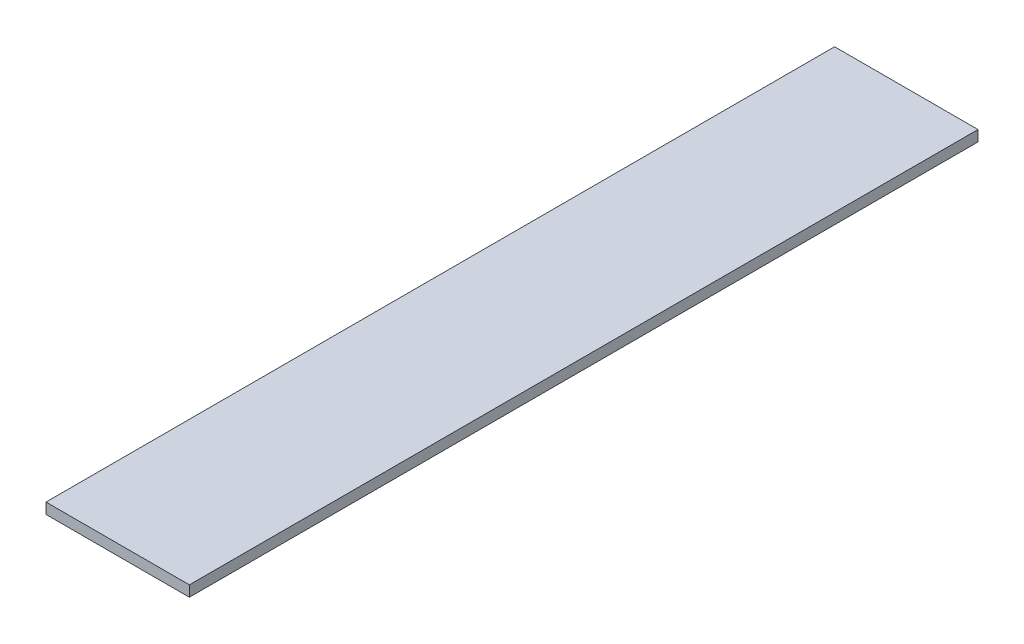
SolidWorks part; units mm, degrees
ref_plane "Front Plane" through (0, 0, 0) normal (0, 0, 1) x (1, 0, 0)
ref_plane "Top Plane" through (0, 0, 0) normal (0, 1, 0) x (1, 0, 0)
ref_plane "Right Plane" through (0, 0, 0) normal (1, 0, 0) x (0, 0, -1)
other "Configuration Table"
sketch "Sketch1" plane through (0, 0, 0) normal (0, 0, 1) x (1, 0, 0)
  line L1 (330, 597) -> (370, 597)
  line L2 (330, 597) -> (330, 600)
  line L3 (330, 600) -> (370, 600)
  line L4 (370, 597) -> (370, 600)
extrude "PACK_orta_ray_yarikli_1" add sketch "Sketch1" against normal blind 220 from offset 570 separate body
